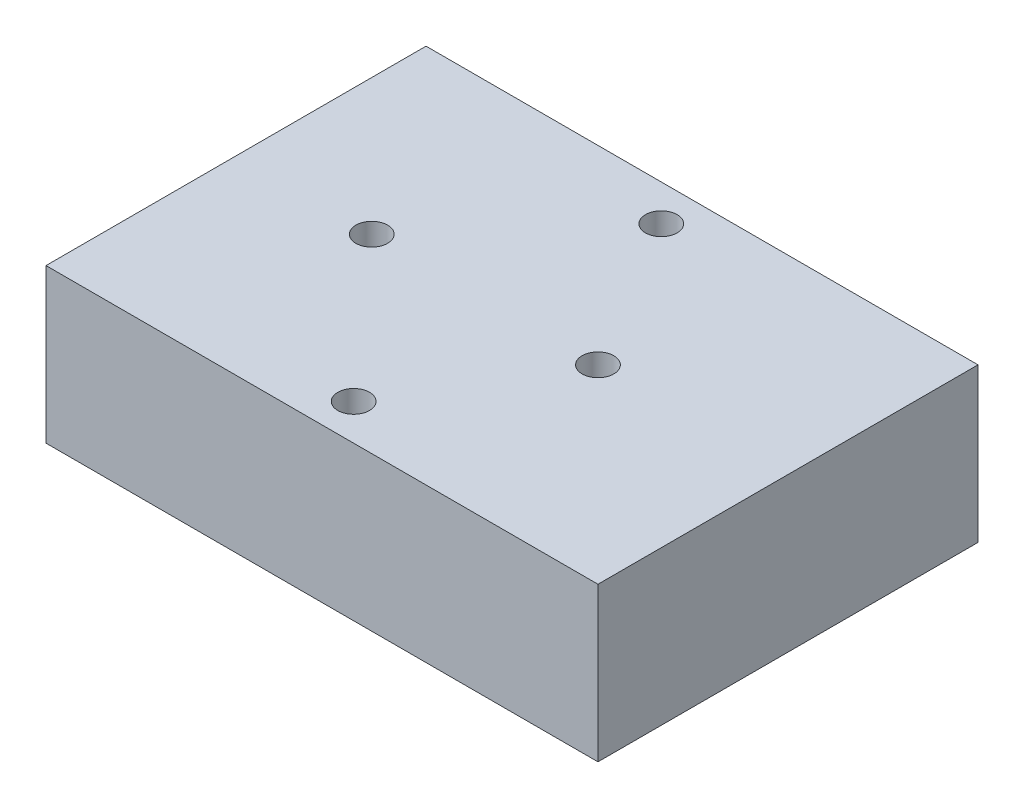
SolidWorks part; units mm, degrees
material "1060 合金"
ref_plane "前视基准面" through (0, 0, 0) normal (0, 0, 1) x (1, 0, 0)
ref_plane "上视基准面" through (0, 0, 0) normal (0, 1, 0) x (1, 0, 0)
ref_plane "右视基准面" through (0, 0, 0) normal (1, 0, 0) x (0, 0, -1)
other "Configuration Table"
sketch "草图1" plane through (0, 0, 0) normal (0, 1, 0) x (1, 0, 0)
  line L1 (-30.5, -21) -> (30.5, -21)
  line L2 (-30.5, -21) -> (-30.5, 21)
  line L3 (-30.5, 21) -> (30.5, 21)
  line L4 (30.5, -21) -> (30.5, 21)
  line L5 (-30.5, -21) -> (30.5, 21) construction
  line L6 (-30.5, 21) -> (30.5, -21) construction
  point P0 (0, 0)
  dimension "D1" = 61
  dimension "D2" = 42
extrude "凸台-拉伸1" add sketch "草图1" along normal blind 17
sketch "草图2" plane through (0, 17, 0) normal (0, 1, 0) x (1, 0, 0)
  line L0 (-30.5, 0) -> (30.5, 0) construction
  line L1 (-30.5, 21) -> (-30.5, -21) construction
  line L2 (30.5, -21) -> (30.5, 21) construction
  line L3 (-0.5, 17) -> (-0.5, -17) construction
  circle A0 centre (-0.5, 17) radius 1.75
  circle A1 centre (-0.5, -17) radius 1.75
  circle A2 centre (-15.5, 0) radius 1.75
  circle A3 centre (9.5, 0) radius 1.75
  dimension "D1" = 3.5
  dimension "D2" = 3.5
  dimension "D6" = 3.5
  dimension "D7" = 3.5
  dimension "D3" = 34
  dimension "D4" = 17
  dimension "D5" = 30
  dimension "D8" = 15
  dimension "D9" = 40
extrude "切除-拉伸1" cut sketch "草图2" against normal blind 17
sketch "草图3" plane through (-30.5, 0, 0) normal (-1, 0, 0) x (0, 0, 1)
  line L0 (-21, 8.5) -> (21, 8.5) construction
  line L1 (-21, 17) -> (-21, 0) construction
  line L2 (21, 17) -> (21, 0) construction
  circle A0 centre (-9, 8.5) radius 2.5
  circle A1 centre (9, 8.5) radius 2.5
  dimension "D3" = 5
  dimension "D4" = 5
  dimension "D1" = 9
  dimension "D2" = 9
extrude "切除-拉伸2" cut sketch "草图3" against normal blind 45
